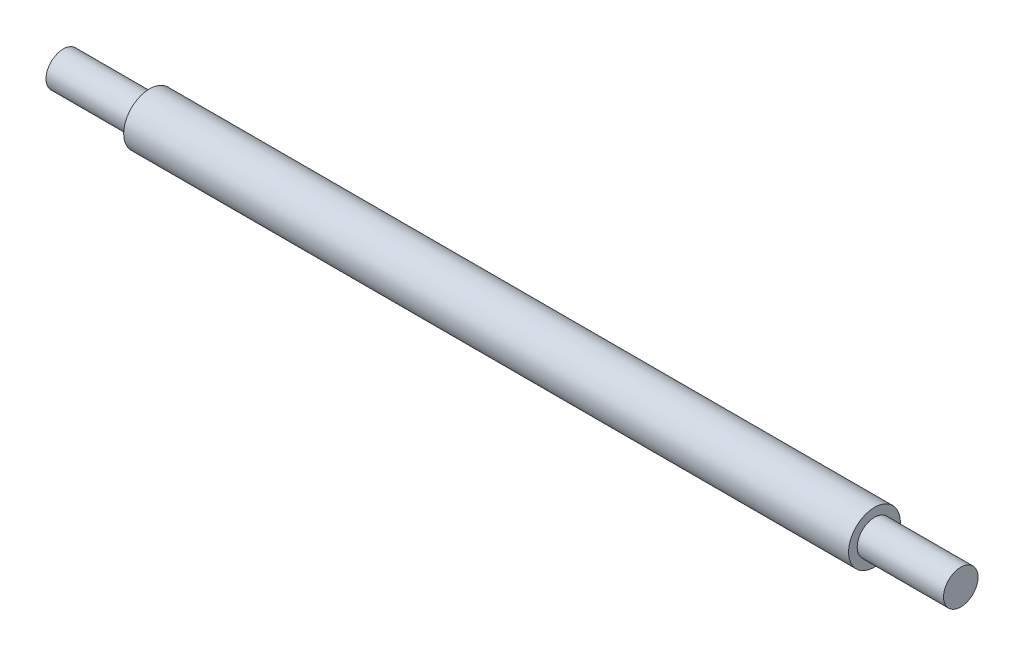
SolidWorks part; units mm, degrees
ref_plane "Front Plane" through (0, 0, 0) normal (0, 0, 1) x (1, 0, 0)
ref_plane "Top Plane" through (0, 0, 0) normal (0, 1, 0) x (1, 0, 0)
ref_plane "Right Plane" through (0, 0, 0) normal (1, 0, 0) x (0, 0, -1)
sketch "Sketch1" plane through (0, 0, 0) normal (0, 0, 1) x (1, 0, 0)
  line L0 (0, 0) -> (104, 0) construction
  line L1 (0, 0) -> (0, 2)
  line L2 (0, 2) -> (10, 2)
  line L3 (10, 2) -> (10, 3)
  line L4 (10, 3) -> (94, 3)
  line L5 (94, 3) -> (94, 2)
  line L6 (94, 2) -> (104, 2)
  line L7 (104, 2) -> (104, 0)
  line L8 (0, 0) -> (104, 0)
  dimension "D1" = 104
  dimension "D2" = 4
  dimension "D3" = 6
  dimension "D4" = 10
revolve "Revolve1" add sketch "Sketch1" angle 360 about L0
ref_plane "Plane1" through (52, 0, 0) normal (1, 0, 0) x (0, 0, -1)
